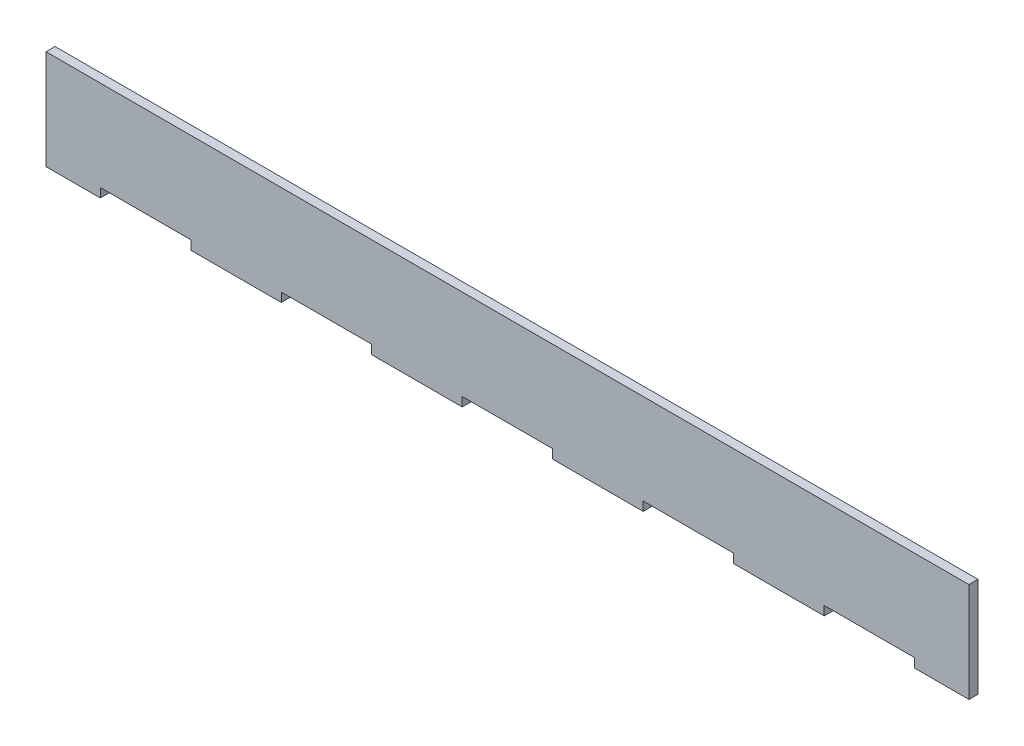
SolidWorks part; units mm, degrees
material "ﾁｰｸ材"
ref_plane "正面" through (0, 0, 0) normal (0, 0, 1) x (1, 0, 0)
ref_plane "平面" through (0, 0, 0) normal (0, 1, 0) x (1, 0, 0)
ref_plane "右側面" through (0, 0, 0) normal (1, 0, 0) x (0, 0, -1)
sketch "ｽｹｯﾁ1" plane through (0, 0, 0) normal (0, 0, 1) x (1, 0, 0)
  line L1 (255, 27.5) -> (-255, 27.5)
  line L2 (255, 27.5) -> (255, -27.5)
  line L3 (255, -27.5) -> (-255, -27.5)
  line L4 (-255, 27.5) -> (-255, -27.5)
  line L5 (255, 27.5) -> (-255, -27.5) construction
  line L6 (255, -27.5) -> (-255, 27.5) construction
  point P0 (0, 0)
  dimension "D1" = 55
  dimension "D2" = 510
extrude "ﾎﾞｽ - 押し出し1" add sketch "ｽｹｯﾁ1" along normal blind 5
sketch "ｽｹｯﾁ2" plane through (0, 0, 5) normal (0, 0, 1) x (1, 0, 0)
  line L0 (-255, -27.5) -> (255, -27.5) construction
  line L1 (-25, -27.5) -> (25, -27.5)
  line L2 (-25, -27.5) -> (-25, -22.5)
  line L3 (-25, -22.5) -> (25, -22.5)
  line L4 (25, -27.5) -> (25, -22.5)
  line L5 (-125, -27.5) -> (-75, -27.5)
  line L6 (75, -27.5) -> (125, -27.5)
  line L7 (75, -27.5) -> (75, -22.5)
  line L8 (75, -22.5) -> (125, -22.5)
  line L9 (125, -27.5) -> (125, -22.5)
  line L10 (-125, -27.5) -> (-125, -22.5)
  line L11 (-125, -22.5) -> (-75, -22.5)
  line L12 (-75, -27.5) -> (-75, -22.5)
  line L13 (175, -27.5) -> (225, -27.5)
  line L14 (175, -27.5) -> (175, -22.5)
  line L15 (175, -22.5) -> (225, -22.5)
  line L16 (225, -27.5) -> (225, -22.5)
  line L17 (-225, -27.5) -> (-175, -27.5)
  line L18 (-225, -27.5) -> (-225, -22.5)
  line L19 (-225, -22.5) -> (-175, -22.5)
  line L20 (-175, -27.5) -> (-175, -22.5)
  point P6 (0, -27.5)
  dimension "D1" = 5
  dimension "D2" = 50
  dimension "D3" = 5
  dimension "D4" = 50
  dimension "D5" = 50
  dimension "D6" = 50
  dimension "D7" = 5
  dimension "D8" = 50
  dimension "D9" = 5
  dimension "D10" = 50
  dimension "D11" = 50
  dimension "D12" = 50
  dimension "D13" = 50
extrude "ｶｯﾄ - 押し出し1" cut sketch "ｽｹｯﾁ2" against normal blind 5
